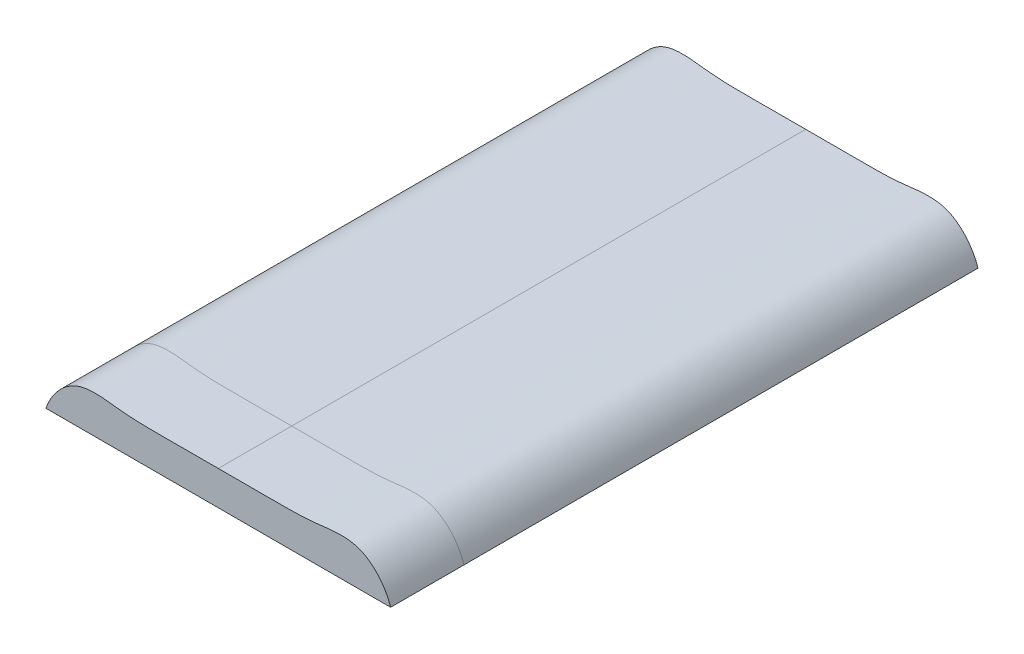
SolidWorks part; units mm, degrees
ref_plane "Plano frontal" through (0, 0, 0) normal (0, 0, 1) x (1, 0, 0)
ref_plane "Plano superior" through (0, 0, 0) normal (0, 1, 0) x (1, 0, 0)
ref_plane "Plano direito" through (0, 0, 0) normal (1, 0, 0) x (0, 0, -1)
sketch "Forma Principal" plane through (0, 0, 0) normal (0, 0, 1) x (1, 0, 0)
  line L0 (20.2, -12.0302) -> (20.2, -10.0302)
  line L1 (0, 6.1527) -> (0, -15) construction
  line L2 (-20.2, -15) -> (-18.7151, -13.5151)
  line L3 (-35.2, -15) -> (-20.2, -15)
  line L4 (-20.2, -10.0302) -> (20.2, -10.0302)
  line L5 (-18.7151, -13.5151) -> (-20.2, -12.0302)
  line L6 (-20.2, -12.0302) -> (-20.2, -10.0302)
  line L7 (18.7151, -13.5151) -> (20.2, -12.0302)
  line L8 (35.2, -15) -> (20.2, -15)
  line L9 (20.2, -15) -> (18.7151, -13.5151)
  spline S0 degree 3 poles (-35.2, -15) (-34.2805, -12.0937) (-29.4244, -5.9702) (-20.5941, -7.9204) (-11.0515, -8.1031) (-4.6374, -7.9876) (0, -8.0302) knots 0 0 0 0 0.248741 0.50777 0.63738 1 1 1 1
  spline S1 degree 3 poles (35.2, -15) (34.2805, -12.0937) (29.4244, -5.9702) (20.5941, -7.9204) (11.0515, -8.1031) (4.6374, -7.9876) (0, -8.0302) knots 0 0 0 0 0.248741 0.50777 0.63738 1 1 1 1
  point P0 (0, 0)
  point P25 (0, -10.0302)
  dimension "D6" = 10
  dimension "D7" = 19
  dimension "D9" = 4
  dimension "D10" = 2
  dimension "D12" = 2.2
  dimension "D13" = 2
  dimension "D8" = 14
  dimension "D3" = 38.793
  dimension "D2" = 20.2
  dimension "D4" = 4
  dimension "D5" = 15
  dimension "D11" = 2
  dimension "D14" = 2.1
  dimension "D15" = 2.1
  dimension "D16" = 45
  dimension "D17" = 15
  dimension "D18" = 7
  dimension "D19" = 2
extrude "Corpo da Tampa" add sketch "Forma Principal" along normal blind 105
sketch "Esboço4" plane through (0, 0, 105) normal (0, 0, 1) x (1, 0, 0)
  line L0 (0, -8.0305) -> (0, -24.8887) construction
  line L2 (-35.2, -15) -> (35.2, -15)
  spline S0 degree 3 poles (-35.2, -15) (-34.2805, -12.0937) (-29.4244, -5.9702) (-20.5941, -7.9204) (-11.0515, -8.1031) (-4.6374, -7.9875) (0, -8.0305) knots 0 0 0 0 0.248741 0.50777 0.63738 1 1 1 1
  spline S1 degree 3 poles (35.2, -15) (34.2805, -12.0937) (29.4244, -5.9702) (20.5941, -7.9204) (11.0515, -8.1031) (4.6374, -7.9875) (0, -8.0305) knots 0 0 0 0 0.248741 0.50777 0.63738 1 1 1 1
  point P17 (0, -15)
  point P22 (0, -10.0305)
  dimension "D7" = 38.793
  dimension "D2" = 35.2
  dimension "D3" = 6.9698
  dimension "D4" = 6.9698
  dimension "D5" = 7.1698
  dimension "D6" = 7.0634
  dimension "D8" = 4
  dimension "D9" = 10
  dimension "D10" = 19
  dimension "D11" = 14
  dimension "D12" = 4
  dimension "D13" = 2
  dimension "D16" = 7
extrude "Tampa Superior" add sketch "Esboço4" along normal blind 15
